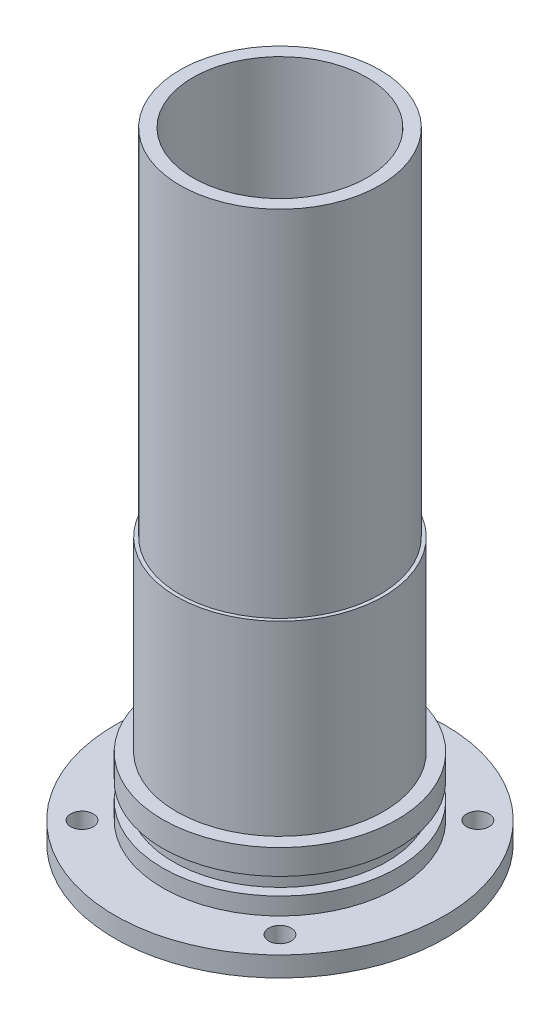
SolidWorks part; units mm, degrees
ref_plane "Front Plane" through (0, 0, 0) normal (0, 0, 1) x (1, 0, 0)
ref_plane "Top Plane" through (0, 0, 0) normal (0, 1, 0) x (1, 0, 0)
ref_plane "Right Plane" through (0, 0, 0) normal (1, 0, 0) x (0, 0, -1)
sketch "Sketch1" plane through (0, 0, 0) normal (0, 0, 1) x (1, 0, 0)
  line L0 (17.4, 0) -> (17.4, 124)
  line L1 (17.4, 124) -> (20, 124)
  line L2 (20, 124) -> (20, 53.1125)
  line L3 (23.45, 4) -> (33, 4)
  line L4 (33, 4) -> (33, 0)
  line L5 (33, 0) -> (17.4, 0)
  line L6 (0, 0) -> (0, 42.2137) construction
  line L7 (23.45, 4) -> (23.45, 7.45)
  line L8 (23.45, 7.45) -> (21.3326, 7.45)
  line L9 (21.3326, 7.45) -> (21.3326, 10.85)
  line L10 (21.3326, 10.85) -> (23.45, 10.85)
  line L11 (23.45, 10.85) -> (23.45, 15.85)
  line L12 (23.45, 15.85) -> (20.7, 15.85)
  line L13 (20.7, 15.85) -> (20.7, 53.1125)
  line L14 (20.7, 53.1125) -> (20, 53.1125)
  point P4 (21.432, 13.9621)
  point P17 (23.8405, 8.4092)
  dimension "D1" = 66
  dimension "D2" = 40
  dimension "D3" = 4
  dimension "D4" = 34.8
  dimension "D5" = 124
  dimension "D6" = 41.4
  dimension "D7" = 11.85
  dimension "D8" = 46.9
  dimension "D9" = 5
  dimension "D10" = 3.4
revolve "Revolve1" add sketch "Sketch1" angle 360 about L6
sketch "Sketch2" plane through (0, 0, 0) normal (0, -1, 0) x (1, 0, 0)
  line L1 (-19.799, -19.799) -> (19.799, -19.799) construction
  line L2 (-19.799, -19.799) -> (-19.799, 19.799) construction
  line L3 (-19.799, 19.799) -> (19.799, 19.799) construction
  line L4 (19.799, -19.799) -> (19.799, 19.799) construction
  line L5 (-19.799, -19.799) -> (19.799, 19.799) construction
  line L6 (-19.799, 19.799) -> (19.799, -19.799) construction
  circle A0 centre (-19.799, 19.799) radius 2.25
  circle A1 centre (19.799, 19.799) radius 2.25
  circle A2 centre (19.799, -19.799) radius 2.25
  circle A3 centre (-19.799, -19.799) radius 2.25
  point P0 (0, 0)
  dimension "D2" = 4.5
  dimension "D1" = 56
extrude "Cut-Extrude1" cut sketch "Sketch2" against normal up to next
